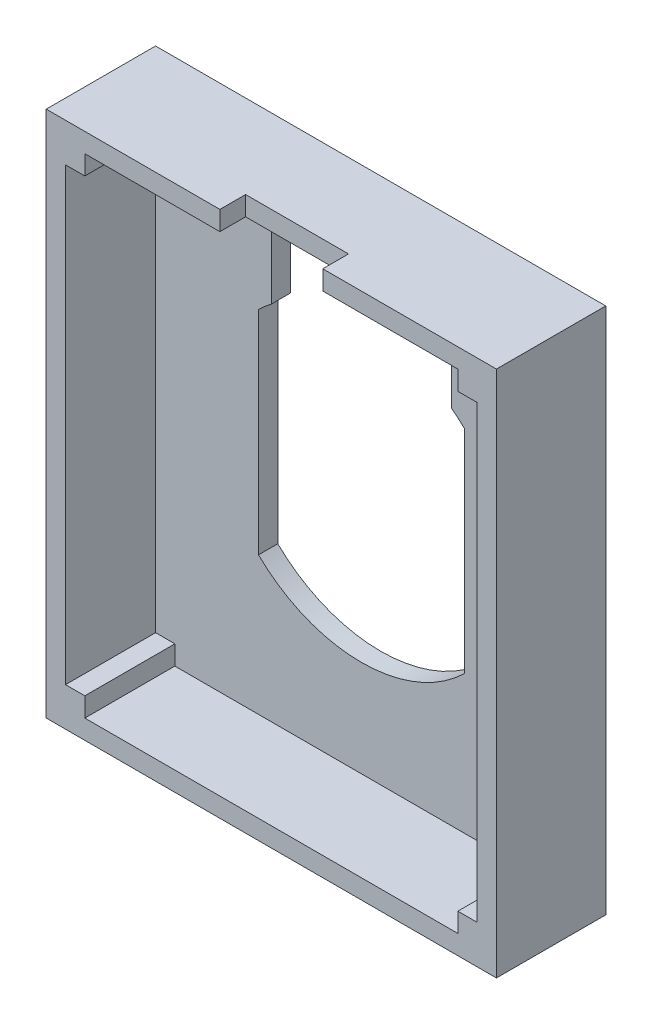
SolidWorks part; units mm, degrees
ref_plane "Спереди" through (0, 0, 0) normal (0, 0, 1) x (1, 0, 0)
ref_plane "Сверху" through (0, 0, 0) normal (0, 1, 0) x (1, 0, 0)
ref_plane "Справа" through (0, 0, 0) normal (1, 0, 0) x (0, 0, -1)
sketch "Эскиз1" plane through (0, 0, 0) normal (0, 0, 1) x (1, 0, 0)
  line L0 (-8, -8.2614) -> (8, 8.2614) construction
  line L1 (0, 15) -> (0, -11.5) construction
  line L2 (15, -18) -> (-15, -18)
  line L3 (15, -18) -> (15, 18)
  line L4 (15, 18) -> (-15, 18)
  line L5 (-15, -18) -> (-15, 18) construction
  line L6 (15, -18) -> (-15, 18) construction
  line L7 (-8, 8.2614) -> (8, -8.2614) construction
  line L8 (7, 9.1241) -> (7, 15)
  line L9 (7, 15) -> (-7, 15)
  line L10 (-7, 9.1241) -> (-7, 15)
  line L11 (15, 18) -> (-15, -18) construction
  line L12 (-8, 0) -> (8, 0) construction
  line L13 (8, -8.2614) -> (8, 8.2614)
  line L14 (17.5, -20.5) -> (17.5, 20.5)
  line L15 (-8, -8.2614) -> (-8, 8.2614)
  line L16 (17.5, 20.5) -> (-17.5, 20.5)
  line L17 (-17.5, -20.5) -> (-17.5, 20.5)
  line L18 (17.5, -20.5) -> (-17.5, -20.5)
  arc A0 (-7, 9.1241) -> (-8, 8.2614) centre (0, 0) ccw
  arc A1 (8, 8.2614) -> (7, 9.1241) centre (0, 0) ccw
  arc A2 (-8, -8.2614) -> (8, -8.2614) centre (0, 0) ccw
  point P0 (0, 0)
  point P9 (8, 0)
  point P12 (0, 11.5)
  point P13 (0, 15)
  dimension "D1" = 23
  dimension "D2" = 14
  dimension "D3" = 30
  dimension "D4" = 18
  dimension "D5" = 16
  dimension "D6" = 2.5
extrude "Бобышка-Вытянуть1" add sketch "Эскиз1" along normal blind 1.5
sketch "Эскиз2" plane through (0, 0, 1.5) normal (0, 0, 1) x (1, 0, 0)
  line L0 (14.5, -19) -> (-14.5, -19)
  line L1 (17.5, -20.5) -> (-17.5, -20.5)
  line L2 (17.5, -20.5) -> (17.5, 20.5)
  line L3 (17.5, 20.5) -> (-17.5, 20.5)
  line L4 (-17.5, -20.5) -> (-17.5, 20.5)
  line L5 (-16, -17.5) -> (-16, 17.5)
  line L6 (14.5, 19) -> (-14.5, 19)
  line L7 (16, -17.5) -> (16, 17.5)
  line L8 (0, 20.5) -> (0, -20.5) construction
  line L9 (-17.5, 20.5) -> (-14.5, 20.5)
  line L10 (-17.5, 20.5) -> (-17.5, 17.5)
  line L11 (-16, 17.5) -> (-14.5, 17.5)
  line L12 (-14.5, 19) -> (-14.5, 17.5)
  line L13 (-16, -19) -> (-16, 19) construction
  line L14 (16, 19) -> (-16, 19) construction
  line L15 (17.5, 0) -> (-17.5, 0) construction
  line L16 (14.5, 19) -> (14.5, 17.5)
  line L17 (16, 17.5) -> (14.5, 17.5)
  line L18 (16, -17.5) -> (14.5, -17.5)
  line L19 (14.5, -19) -> (14.5, -17.5)
  line L20 (-14.5, -19) -> (-14.5, -17.5)
  line L21 (-16, -17.5) -> (-14.5, -17.5)
  line L23 (16, -19) -> (-16, -19) construction
  line L24 (16, -19) -> (16, 19) construction
  line M13 (-17.5, -20.5) -> (17.5, -20.5)
  line M14 (17.5, -20.5) -> (17.5, 20.5)
  line M15 (17.5, 20.5) -> (-17.5, 20.5)
  line M16 (-17.5, 20.5) -> (-17.5, -20.5)
  dimension "D2" = 3
  dimension "D3" = 3
  dimension "D1" = 1.5
extrude "Бобышка-Вытянуть2" add sketch "Эскиз2" along normal blind 7 contours L4 L3 L21 L5 L11 L12 L6 L16 L17 L7 L18 L19 L0 L20 M16 M13 M14 M15
sketch "Эскиз3" plane through (0, 0, 8.5) normal (0, 0, 1) x (1, 0, 0)
  line L0 (14.5, 19) -> (-14.5, 19) construction
  line L1 (14.5, 19) -> (-14.5, 19) construction
  line L3 (4, 19) -> (4, 20.5)
  line L4 (4, 20.5) -> (-4, 20.5)
  line L5 (-4, 19) -> (-4, 20.5)
  line L8 (17.5, 20.5) -> (-17.5, 20.5) construction
  line L9 (-4, 19) -> (4, 19)
  point P0 (0, 19)
  point P1 (0, 19)
extrude "Вырез-Вытянуть1" cut sketch "Эскиз3" against normal blind 2
